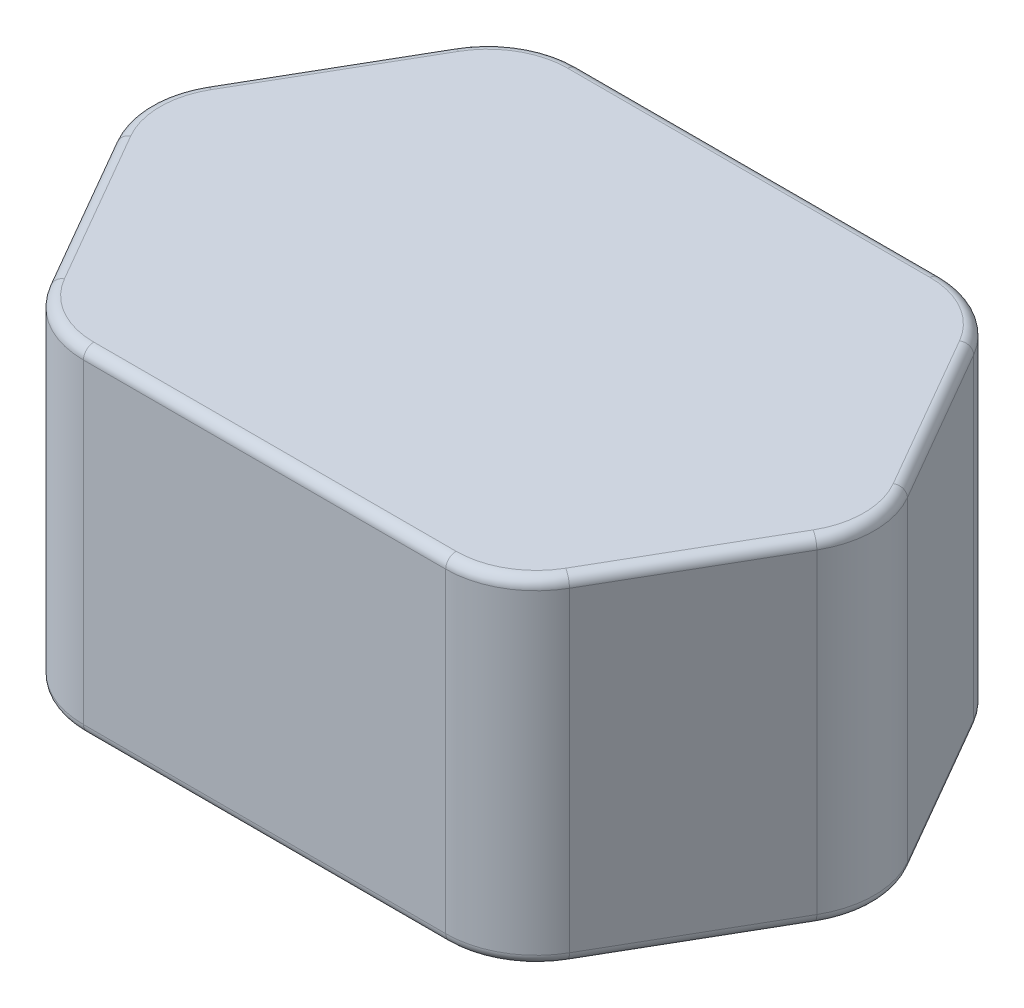
SolidWorks part; units mm, degrees
material "Polyurethane"
ref_plane "Plan de face" through (0, 0, 0) normal (0, 0, 1) x (1, 0, 0)
ref_plane "Plan de dessus" through (0, 0, 0) normal (0, 1, 0) x (1, 0, 0)
ref_plane "Plan de droite" through (0, 0, 0) normal (1, 0, 0) x (0, 0, -1)
sketch "Sketch1" plane through (0, 0, 0) normal (0, 1, 0) x (1, 0, 0)
  line L0 (0, 0) -> (17.5, -30.3109) construction
  line L1 (17.5, -30.3109) -> (52.5, -30.3109) construction
  line L2 (52.5, -30.3109) -> (87.5, -30.3109) construction
  line L3 (70, 0) -> (105, 0) construction
  line L4 (87.5, 30.3109) -> (52.5, 30.3109) construction
  line L5 (52.5, 30.3109) -> (17.5, 30.3109) construction
  line L6 (17.5, 30.3109) -> (0, 0) construction
  line L7 (0, 0) -> (35, 0) construction
  line L8 (35, 0) -> (70, 0) construction
  line L9 (105, 0) -> (87.5, 30.3109) construction
  line L10 (105, 0) -> (87.5, -30.3109) construction
  line L11 (35, 0) -> (17.5, -30.3109) construction
  line L12 (-15.1554, 8.75) -> (2.3446, 39.0609)
  line L13 (17.5, 47.8109) -> (87.5, 47.8109)
  line L14 (102.6554, 39.0609) -> (120.1554, 8.75)
  line L15 (120.1554, -8.75) -> (102.6554, -39.0609)
  line L16 (87.5, -47.8109) -> (17.5, -47.8109)
  line L17 (2.3446, -39.0609) -> (-15.1554, -8.75)
  arc A0 (-15.1554, 8.75) -> (-15.1554, -8.75) centre (0, 0) ccw
  arc A1 (2.3446, -39.0609) -> (17.5, -47.8109) centre (17.5, -30.3109) ccw
  arc A3 (87.5, -47.8109) -> (102.6554, -39.0609) centre (87.5, -30.3109) ccw
  arc A4 (102.6554, 39.0609) -> (87.5, 47.8109) centre (87.5, 30.3109) ccw
  arc A6 (17.5, 47.8109) -> (2.3446, 39.0609) centre (17.5, 30.3109) ccw
  arc A9 (120.1554, -8.75) -> (120.1554, 8.75) centre (105, 0) ccw
  dimension "D1" = 35
  dimension "D2" = 35
extrude "Extrude1" add sketch "Sketch1" along normal blind 65
fillet "Fillet1" radius 2 24 edges at (-6.4054, 0, 23.9054) (8.75, 0, 45.4663) (52.5, 0, 47.8109) (96.25, 0, 45.4663) (111.4054, 0, 23.9054) (122.5, 0, 0) (111.4054, 0, -23.9054) (96.25, 0, -45.4663) (52.5, 0, -47.8109) (8.75, 0, -45.4663) (-6.4054, 0, -23.9054) (-17.5, 0, 0) (-6.4054, 65, -23.9054) (8.75, 65, -45.4663) (52.5, 65, -47.8109) (96.25, 65, -45.4663) (111.4054, 65, -23.9054) (122.5, 65, 0) (111.4054, 65, 23.9054) (96.25, 65, 45.4663) (52.5, 65, 47.8109) (8.75, 65, 45.4663) (-6.4054, 65, 23.9054) (-17.5, 65, 0)
